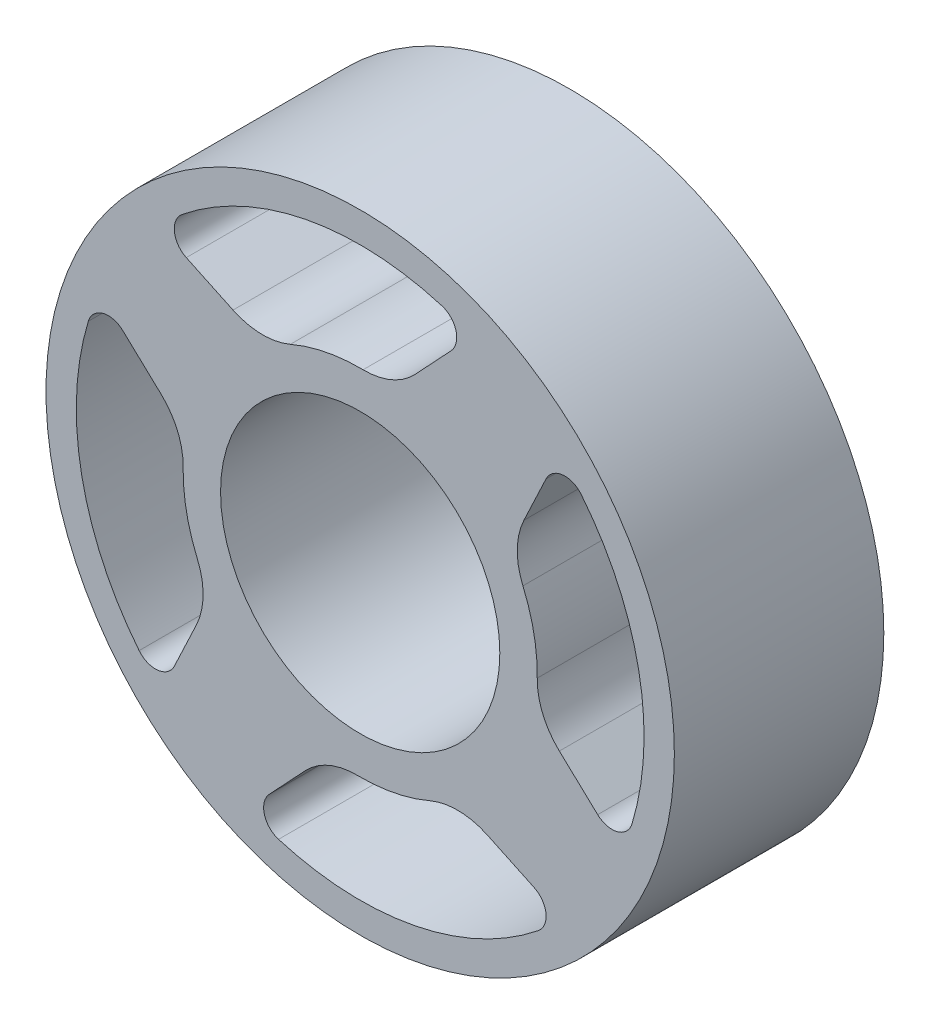
SolidWorks part; units mm, degrees
ref_plane "Front Plane" through (0, 0, 0) normal (0, 0, 1) x (1, 0, 0)
ref_plane "Top Plane" through (0, 0, 0) normal (0, 1, 0) x (1, 0, 0)
ref_plane "Right Plane" through (0, 0, 0) normal (1, 0, 0) x (0, 0, -1)
sketch "Sketch1" plane through (0, 0, 0) normal (0, 0, 1) x (1, 0, 0)
  circle A0 centre (0, 0) radius 20
  circle A1 centre (0, 0) radius 45
  dimension "D1" = 40
  dimension "D2" = 90
extrude "Boss-Extrude1" add sketch "Sketch1" along normal blind 30
sketch "Sketch2" plane through (0, 0, 30) normal (0, 0, 1) x (1, 0, 0)
  line L0 (-24.9076, 26.6105) -> (-18.2114, 23.453)
  line L1 (7.8806, 28.5257) -> (13.0209, 34.0176)
  line L2 (28.5257, -7.8806) -> (34.0176, -13.0209)
  line L3 (26.6105, 24.9076) -> (23.453, 18.2114)
  line L4 (-7.8806, -28.5257) -> (-13.0209, -34.0176)
  line L5 (24.9076, -26.6105) -> (18.2114, -23.453)
  line L6 (-28.5257, 7.8806) -> (-34.0176, 13.0209)
  line L7 (-26.6105, -24.9076) -> (-23.453, -18.2114)
  arc A0 (-25.5103, 31.66) -> (11.6935, 38.9409) centre (0, 0) cw
  arc A1 (-10.0027, 23.3083) -> (0.4158, 25.3606) centre (0, 0) cw
  arc A2 (-10.0027, 23.3083) -> (-18.2114, 23.453) centre (-13.9464, 32.4978) cw
  arc A3 (0.4158, 25.3606) -> (7.8806, 28.5257) centre (0.5797, 35.3592) ccw
  arc A4 (-25.5103, 31.66) -> (-24.9076, 26.6105) centre (-23.628, 29.324) ccw
  arc A5 (13.0209, 34.0176) -> (11.6935, 38.9409) centre (10.8307, 36.0677) ccw
  arc A6 (31.66, 25.5103) -> (38.9409, -11.6935) centre (0, 0) cw
  arc A7 (34.0176, -13.0209) -> (38.9409, -11.6935) centre (36.0677, -10.8307) ccw
  arc A8 (25.3606, -0.4158) -> (28.5257, -7.8806) centre (35.3592, -0.5797) ccw
  arc A9 (23.3083, 10.0027) -> (25.3606, -0.4158) centre (0, 0) cw
  arc A10 (23.3083, 10.0027) -> (23.453, 18.2114) centre (32.4978, 13.9464) cw
  arc A11 (31.66, 25.5103) -> (26.6105, 24.9076) centre (29.324, 23.628) ccw
  arc A12 (25.5103, -31.66) -> (-11.6935, -38.9409) centre (0, 0) cw
  arc A13 (-13.0209, -34.0176) -> (-11.6935, -38.9409) centre (-10.8307, -36.0677) ccw
  arc A14 (-0.4158, -25.3606) -> (-7.8806, -28.5257) centre (-0.5797, -35.3592) ccw
  arc A15 (10.0027, -23.3083) -> (-0.4158, -25.3606) centre (0, 0) cw
  arc A16 (10.0027, -23.3083) -> (18.2114, -23.453) centre (13.9464, -32.4978) cw
  arc A17 (25.5103, -31.66) -> (24.9076, -26.6105) centre (23.628, -29.324) ccw
  arc A18 (-31.66, -25.5103) -> (-38.9409, 11.6935) centre (0, 0) cw
  arc A19 (-34.0176, 13.0209) -> (-38.9409, 11.6935) centre (-36.0677, 10.8307) ccw
  arc A20 (-25.3606, 0.4158) -> (-28.5257, 7.8806) centre (-35.3592, 0.5797) ccw
  arc A21 (-23.3083, -10.0027) -> (-25.3606, 0.4158) centre (0, 0) cw
  arc A22 (-23.3083, -10.0027) -> (-23.453, -18.2114) centre (-32.4978, -13.9464) cw
  arc A23 (-31.66, -25.5103) -> (-26.6105, -24.9076) centre (-29.324, -23.628) ccw
  point P53 (0, 0)
  dimension "D1" = 10
  dimension "D2" = 10
  dimension "D3" = 3
  dimension "D4" = 6
  dimension "D5" = 4
extrude "Cut-Extrude1" cut sketch "Sketch2" against normal blind 30
